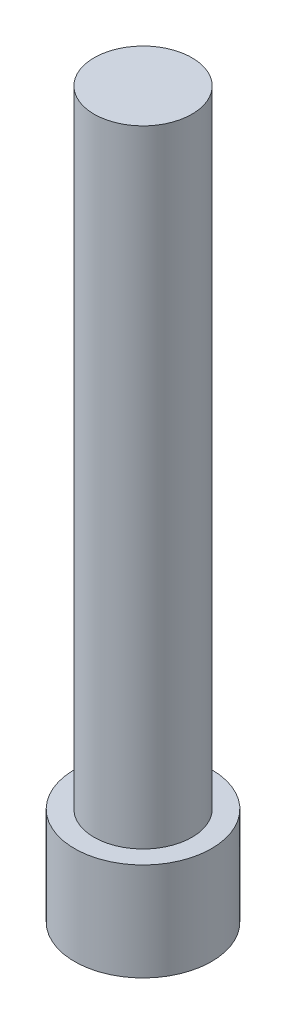
SolidWorks part; units mm, degrees
ref_plane "前视基准面" through (0, 0, 0) normal (0, 0, 1) x (1, 0, 0)
ref_plane "上视基准面" through (0, 0, 0) normal (0, 1, 0) x (1, 0, 0)
ref_plane "右视基准面" through (0, 0, 0) normal (1, 0, 0) x (0, 0, -1)
sketch "草图1" plane through (0, 0, 0) normal (0, 1, 0) x (1, 0, 0)
  circle A0 centre (0, 0) radius 2.5
extrude "凸台-拉伸1" add sketch "草图1" along normal blind 32
sketch "草图2" plane through (0, 0, 0) normal (0, -1, 0) x (1, 0, 0)
  circle A0 centre (0, 0) radius 3.5
extrude "凸台-拉伸2" add sketch "草图2" along normal blind 5
